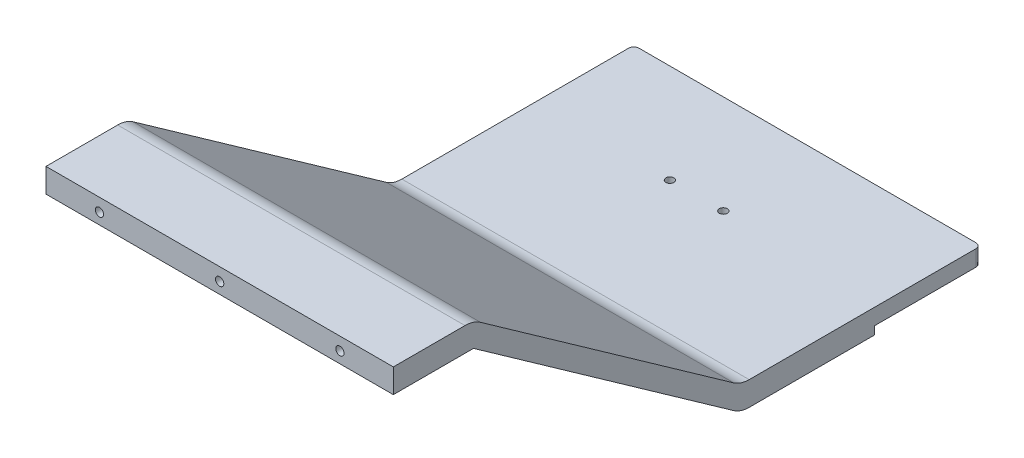
SolidWorks part; units mm, degrees
ref_plane "前视基准面" through (0, 0, 0) normal (0, 0, 1) x (1, 0, 0)
ref_plane "上视基准面" through (0, 0, 0) normal (0, 1, 0) x (1, 0, 0)
ref_plane "右视基准面" through (0, 0, 0) normal (1, 0, 0) x (0, 0, -1)
other "Configuration Table"
sketch "草图1" plane through (0, 0, 0) normal (0, 0, 1) x (1, 0, 0)
  line L0 (0, 0) -> (0, 79)
  line L1 (0, 79) -> (79, 79)
  line L2 (79, 79) -> (79, 70)
  line L3 (79, 70) -> (9, 70)
  line L4 (9, 70) -> (9, 0)
  line L5 (9, 0) -> (0, 0)
  dimension "D1" = 9
  dimension "D2" = 9
  dimension "D3" = 70
  dimension "D4" = 70
ref_plane "基准面1" through (0, 0, 100) normal (0, 0, 1) x (1, 0, 0)
sketch "草图2" plane through (0, 0, 100) normal (0, 0, 1) x (1, 0, 0)
  line L0 (0, 79) -> (-70.7107, 149.7107) construction
  line L1 (0, 0) -> (0, 79) construction
  line L2 (-70.7107, 149.7107) -> (-70.7107, 0)
  line L3 (-70.7107, 0) -> (-61.7107, 0)
  line L4 (-61.7107, 0) -> (-61.7107, 140.7107)
  line L5 (-61.7107, 140.7107) -> (79, 140.7107)
  line L6 (79, 140.7107) -> (79, 149.7107)
  line L7 (79, 149.7107) -> (-70.7107, 149.7107)
  line L8 (0, 0) -> (0, 79) construction
  line L9 (0, 79) -> (79, 79) construction
  dimension "D1" = 135
  dimension "D2" = 9
  dimension "D3" = 100
  dimension "D4" = 79
loft "放样1" add profiles "草图1", "草图2"
sketch "草图4" plane through (0, 0, 0) normal (0, 0, -1) x (-1, 0, 0)
  line L7 (-9, 0) -> (0, 0)
  line L8 (0, 0) -> (0, 79)
  line L9 (0, 79) -> (-79, 79)
  line L10 (-79, 79) -> (-79, 70)
  line L11 (-79, 70) -> (-77.7656, 70)
  line L12 (-77.7656, 70) -> (-9, 70)
  line L13 (-9, 70) -> (-9, 0)
  line L14 (-9, 0) -> (0, 0)
  line L15 (0, 0) -> (0, 79)
  line L16 (0, 79) -> (-79, 79)
  line L17 (-79, 79) -> (-79, 70)
  line L18 (-79, 70) -> (-77.7656, 70)
  line L19 (-77.7656, 70) -> (-9, 70)
  line L20 (-9, 70) -> (-9, 0)
  dimension "D1" = 0
extrude "凸台-拉伸1" add sketch "草图4" along normal blind 50
sketch "草图9" plane through (0, 0, -50) normal (0, 0, -1) x (-1, 0, 0)
  line L0 (-9, 70) -> (-9, 0) construction
  line L1 (-9, 70) -> (-55, 70)
  line L2 (-9, 70) -> (-9, 30)
  line L3 (-15, 64) -> (-55, 64)
  line L4 (-55, 70) -> (-55, 64)
  line L6 (-15, 64) -> (-15, 30)
  line L7 (-15, 30) -> (-9, 30)
  dimension "D1" = 6
  dimension "D2" = 46
  dimension "D3" = 6
  dimension "D4" = 40
extrude "凸台-拉伸3" add sketch "草图9" against normal blind 6
fillet "圆角1" radius 10 7 edges
sketch "草图11" plane through (0, 0, -44) normal (0, 0, 1) x (1, 0, 0)
  circle A0 centre (12, 45) radius 1.55
  circle A1 centre (12, 65) radius 1.55
  circle A2 centre (30, 67) radius 1.55
  circle A3 centre (50, 67) radius 1.55
  dimension "D1" = 3.1
extrude "切除-拉伸1" cut sketch "草图11" against normal through all
sketch "草图12" plane through (0, 0, -50) normal (0, 0, -1) x (-1, 0, 0)
  line L0 (0, 19) -> (0, 0)
  line L1 (0, 0) -> (0, 69) construction
  line L2 (0, 0) -> (-6, 0)
  line L3 (-9, 0) -> (0, 0) construction
  line L5 (-6, 0) -> (-6, 19)
  line L6 (0, 19) -> (-6, 19)
  line L7 (-2.9289, 76.0711) -> (-93.7798, -14.7798) construction
  line L8 (0, 0) -> (0, 69) construction
  line L9 (-60, 79) -> (-60, 73)
  line L10 (-79, 73) -> (-60, 73)
  line L11 (-79, 79) -> (-79, 73)
  line L12 (-60, 79) -> (-79, 79)
  arc A0 (0, 69) -> (-10, 79) centre (-10, 69) ccw construction
  dimension "D1" = 19
  dimension "D2" = 6
  dimension "D3" = 45
extrude "凸台-拉伸4" add sketch "草图12" along normal blind 40
fillet "圆角2" radius 2 9 edges at (3, 0, -90) (3, 19, -90) (9, 30, -47) (15, 30, -47) (15, 64, -47) (55, 70, -47) (55, 64, -47) (79, 76, -90) (60, 76, -90)
sketch "草图13" plane through (79, 0, 0) normal (1, 0, 0) x (0, 0, -1)
  line L0 (90, 79) -> (88, 79) construction
  line L1 (90, 79) -> (90, 73) construction
  line L9 (50, 73) -> (88, 73)
  line L10 (88, 73) -> (88, 79)
  line L11 (88, 79) -> (3.1784, 79)
  line L12 (-2.5951, 80.835) -> (-100, 149.7107)
  line L13 (-100, 149.7107) -> (-100, 149.2162)
  line L14 (-100, 149.2162) -> (-100, 140.7107)
  line L15 (-100, 140.7107) -> (-2.5951, 71.835)
  line L16 (3.1784, 70) -> (50, 70)
  line L17 (50, 70) -> (50, 73)
  line L18 (50, 73) -> (90, 73)
  line L19 (90, 73) -> (90, 79)
  line L20 (90, 79) -> (3.1784, 79)
  line L21 (-2.5951, 80.835) -> (-100, 149.7107)
  line L22 (-100, 149.7107) -> (-100, 149.2162)
  line L23 (-100, 149.2162) -> (-100, 140.7107)
  line L24 (-100, 140.7107) -> (-2.5951, 71.835)
  line L25 (3.1784, 70) -> (50, 70)
  line L26 (50, 70) -> (50, 73)
  arc A2 (-2.5951, 80.835) -> (3.1784, 79) centre (3.1784, 89) ccw
  arc A3 (-2.5951, 71.835) -> (3.1784, 70) centre (3.1784, 80) ccw
  arc A4 (-2.5951, 80.835) -> (3.1784, 79) centre (3.1784, 89) ccw
  arc A5 (-2.5951, 71.835) -> (3.1784, 70) centre (3.1784, 80) ccw
  dimension "D1" = 0
extrude "凸台-拉伸5" add sketch "草图13" along normal blind 130 separate body
delete or keep bodies "实体-删除/保留 1" type delete bodies bodies 112
sketch "草图14" plane through (0, 0, 100) normal (0, 0, 1) x (1, 0, 0)
  line L4 (79, 149.7107) -> (79, 140.7107)
  line L5 (79, 140.7107) -> (209, 140.7107)
  line L6 (209, 140.7107) -> (209, 149.7107)
  line L7 (209, 149.7107) -> (79, 149.7107)
  line L8 (79, 149.7107) -> (79, 140.7107)
  line L9 (79, 140.7107) -> (209, 140.7107)
  line L10 (209, 140.7107) -> (209, 149.7107)
  line L11 (209, 149.7107) -> (79, 149.7107)
  dimension "D1" = 0
extrude "凸台-拉伸6" add sketch "草图14" along normal blind 30
sketch "草图15" plane through (0, 0, 130) normal (0, 0, 1) x (1, 0, 0)
  line L0 (79, 149.7107) -> (79, 140.7107) construction
  line L1 (79, 140.7107) -> (209, 140.7107) construction
  circle A0 centre (99, 144.8907) radius 1.55
  circle A1 centre (144, 144.8907) radius 1.55
  circle A2 centre (189, 144.8907) radius 1.55
  dimension "D1" = 3.1
  dimension "D2" = 20
  dimension "D3" = 4.18
  dimension "D5" = 45
  dimension "D4" = 3
extrude "切除-拉伸2" cut sketch "草图15" against normal blind 5
fillet "圆角3" radius 2 2 edges at (79, 76, -90) (209, 76, -90)
sketch "草图16" plane through (0, 73, 0) normal (0, -1, 0) x (1, 0, 0)
  line L1 (144, 130) -> (144, 82.7932) construction
  line L2 (79, 130) -> (209, 130) construction
  line L3 (209, -50) -> (79, -50) construction
  circle A1 centre (149.5, -53) radius 1.5
  circle A2 centre (129.5, -53) radius 1.5
  dimension "D1" = 3
  dimension "D2" = 3
  dimension "D3" = 5.5
  dimension "D4" = 20
extrude "切除-拉伸3" cut sketch "草图16" against normal through all
fillet "圆角4" radius 10 1 edges at (144, 149.7107, 100)
